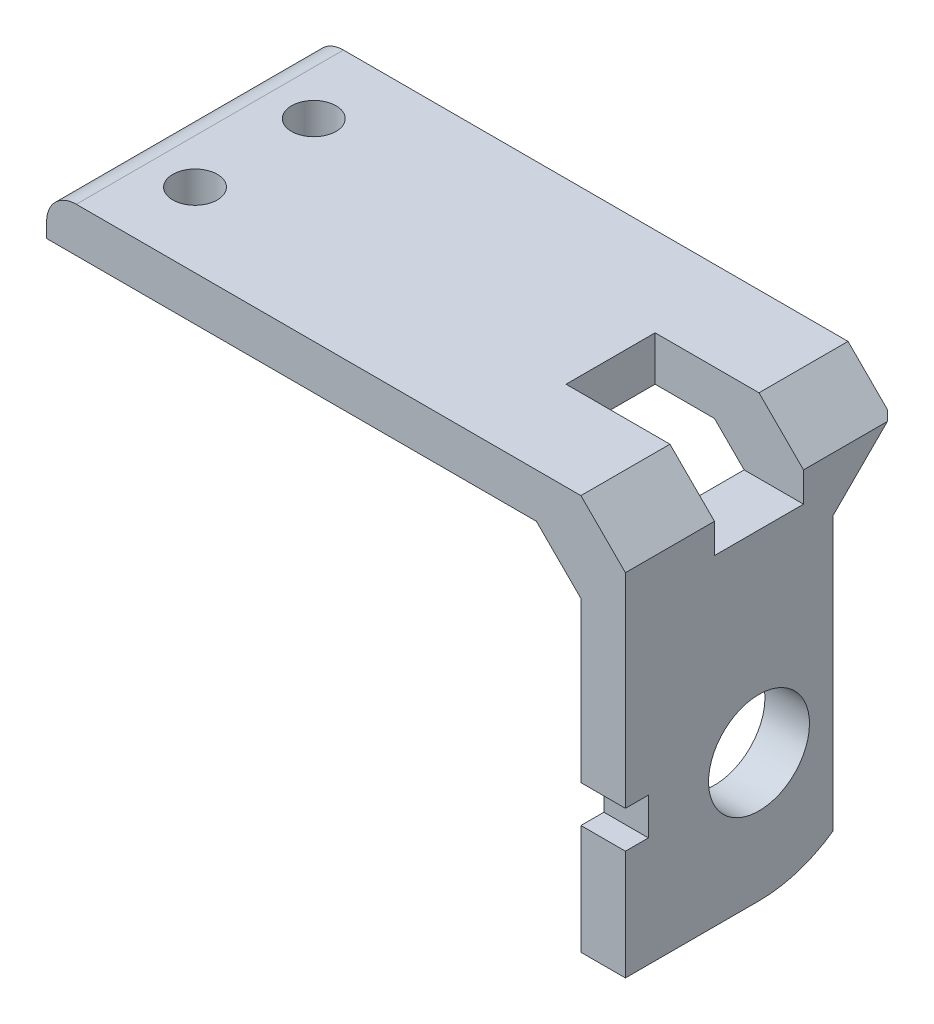
SolidWorks part; units mm, degrees
ref_plane "Alzado" through (0, 0, 0) normal (0, 0, 1) x (1, 0, 0)
ref_plane "Planta" through (0, 0, 0) normal (0, 1, 0) x (1, 0, 0)
ref_plane "Vista lateral" through (0, 0, 0) normal (1, 0, 0) x (0, 0, -1)
sketch "Croquis1" plane through (0, 0, 0) normal (0, 0, 1) x (1, 0, 0)
  line L0 (0, -6.3501) -> (0, 20.6499)
  line L1 (0, 20.6499) -> (-36, 20.6499)
  line L2 (-36, 20.6499) -> (-36, 21.6499)
  line L3 (-34, 23.6499) -> (3, 23.6499)
  line L4 (3, 23.6499) -> (3, -6.3501)
  line L5 (3, -6.3501) -> (0, -6.3501)
  arc A0 (-34, 23.6499) -> (-36, 21.6499) centre (-34, 21.6499) ccw
  point P11 (-36, 23.6499)
  dimension "D1" = 2
  dimension "D2" = 3
  dimension "D3" = 3
  dimension "D4" = 30
extrude "Saliente-Extruir1" add sketch "Croquis1" along normal blind 18
sketch "Croquis2" plane through (3, 0, 0) normal (1, 0, 0) x (0, 0, -1)
  line L0 (-18, 23.6499) -> (0, 23.6499) construction
  line L1 (-18, 20.6499) -> (0, 20.6499) construction
  circle A0 centre (-9, 5.6499) radius 3.4
  point P7 (-9, 23.6499)
  dimension "D1" = 6.8
  dimension "D2" = 15
extrude "Cortar-Extruir1" cut sketch "Croquis2" against normal blind 22
sketch "Croquis3" plane through (0, 23.6499, 0) normal (0, 1, 0) x (1, 0, 0)
  line L0 (-36, -18) -> (-36, 0) construction
  line L1 (-37, -9) -> (49963, -9) construction
  line L2 (3, 0) -> (-34, 0) construction
  circle A0 centre (-31, -5) radius 1.5
  circle A1 centre (-31, -13) radius 1.5
  point P7 (-36, -9)
  dimension "D1" = 5
  dimension "D2" = 3
  dimension "D3" = 5
extrude "Cortar-Extruir2" cut sketch "Croquis3" against normal blind 22
sketch "Croquis4" plane through (0, 0, 0) normal (-1, 0, 0) x (0, 0, 1)
  line L0 (0, 20.9999) -> (4, 16.9999)
  line L1 (0, 20.6499) -> (0, -6.3501) construction
  line L2 (17.65, 16.9999) -> (0.35, 16.9999) construction
  line L3 (4, 16.9999) -> (4, -1.4087)
  line L4 (9, -3.0001) -> (18, -3.0001)
  line L5 (18, 20.6499) -> (18, -6.3501) construction
  line L6 (18, -3.0001) -> (18, -6.3501)
  line L7 (18, -6.3501) -> (0, -6.3501)
  line L8 (0, -6.3501) -> (0, 20.9999)
  line L10 (16.45, 6.8999) -> (18, 6.8999)
  line L11 (16.45, 6.8999) -> (16.45, 4.3999)
  line L12 (16.45, 4.3999) -> (18, 4.3999)
  line L13 (18, 6.8999) -> (18, 4.3999)
  arc A0 (2.3237, 0.1499) -> (15.6763, 0.1499) centre (9, 5.6499) ccw construction
  arc A1 (4, -1.4087) -> (9, -3.0001) centre (9, 5.6499) ccw
  dimension "D1" = 45
  dimension "D2" = 4
extrude "Cortar-Extruir3" cut sketch "Croquis4" against normal through all
chamfer "Chaflán1" distance 3 angle 45 2 edges at (3, 23.6499, 9) (0, 20.6499, 9.175)
sketch "Croquis5" plane through (0, 23.6499, 0) normal (0, 1, 0) x (1, 0, 0)
  line L0 (3, -0.35) -> (3, -18) construction
  line L1 (-7, -6) -> (3, -6)
  line L2 (-7, -6) -> (-7, -12)
  line L3 (-7, -12) -> (3, -12)
  line L4 (3, -6) -> (3, -12)
  line L5 (0, 0) -> (-34, 0) construction
  line L6 (0, -18) -> (-34, -18) construction
  dimension "D1" = 10
  dimension "D2" = 6
  dimension "D3" = 6
extrude "Cortar-Extruir4" cut sketch "Croquis5" against normal blind 5
